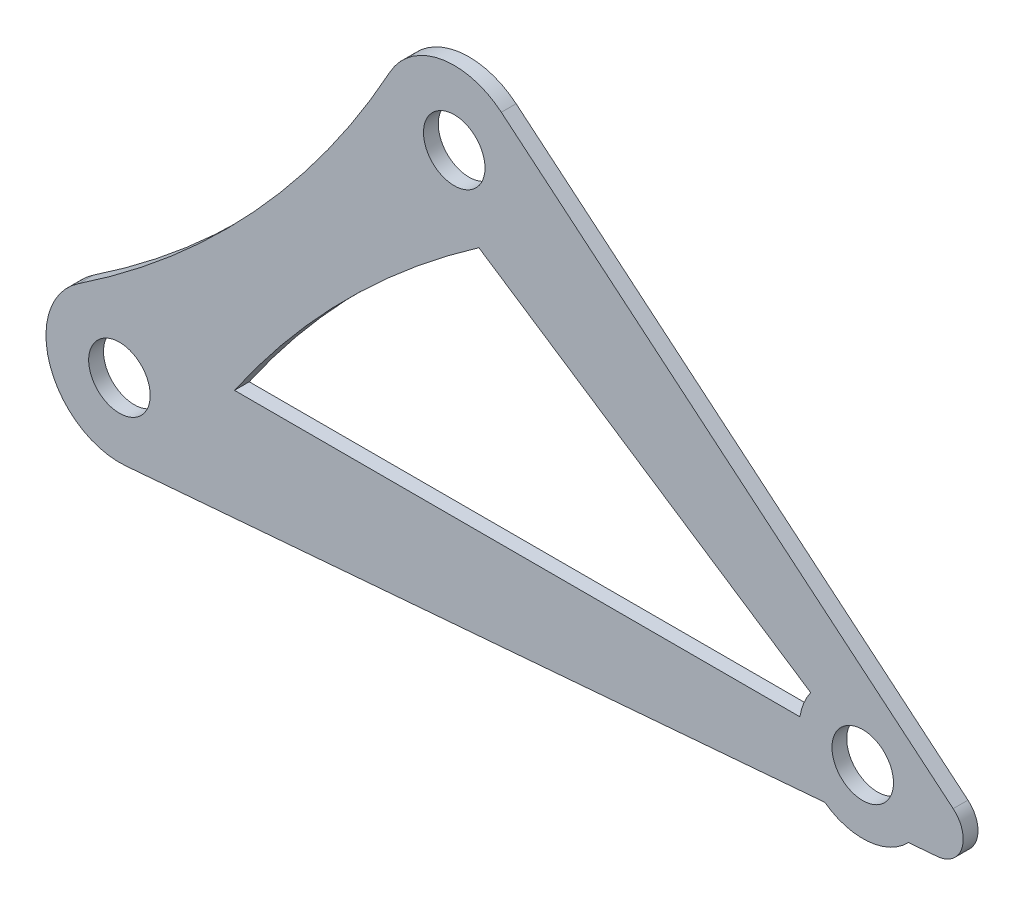
SolidWorks part; units mm, degrees
ref_plane "Plan de face" through (0, 0, 0) normal (1, 0, 0) x (0, 1, 0)
ref_plane "Plan de dessus" through (0, 0, 0) normal (0, 0, 1) x (0, 1, 0)
ref_plane "Plan de droite" through (0, 0, 0) normal (0, 1, 0) x (-1, 0, 0)
sketch "Esquisse1" plane through (0, 0, 0) normal (0, 0, 1) x (0, 1, 0)
  line L0 (0, 0) -> (0, 95.09) construction
  line L1 (0, 95.09) -> (39.1116, 59.1602) construction
  line L2 (39.1116, 59.1602) -> (0, 0) construction
  line L3 (0, 0) -> (19.5558, 77.1251) construction
  line L7 (0, 0) -> (-7.8578, 94.4362)
  line L8 (0, 0) -> (45.1649, 54.1073)
  line L9 (31.5783, 56.8316) -> (5.8767, 17.9555)
  line L10 (5, 18.4299) -> (5, 88.993)
  line L11 (34.9407, 61.9176) -> (5, 16.6293) construction
  line L13 (5, 16.6293) -> (5, 95.09) construction
  circle A0 centre (0, 95.09) radius 3.302
  circle A1 centre (39.1116, 59.1602) radius 3.302
  circle A3 centre (0, 95.09) radius 7.885
  circle A4 centre (39.1116, 59.1602) radius 7.885
  circle A6 centre (3.885, 15.3218) radius 3.302
  circle A7 centre (3.885, 15.3218) radius 3.885 construction
  circle A8 centre (3.885, 15.3218) radius 6.836
  arc A9 (42.9154, 66.067) -> (6.5601, 99.4647) centre (93.0851, 157.1659) cw
  arc A10 (32.5515, 54.7854) -> (-3.8037, 88.1831) centre (-53.9735, -2.9157) ccw
  dimension "D4" = 6.604
  dimension "D5" = 7.77
  dimension "D6" = 15.77
  dimension "D9" = 104
  dimension "D1" = 95.09
  dimension "D2" = 70.92
  dimension "D3" = 53.11
  dimension "D8" = 5
extrude "Boss.-Extru.2" add sketch "Esquisse1" along normal blind 1.587 contours L7 A8 | L10 A10 A3 L7 A8 | A4 A1 | A10 L9 A4 A9 A3 L10 | A10 L10 A3 | A3 A0 | L9 A8 L10 A6 | L10 A8 L7 L9 A6 | A4 A10 L9 A8 L7 L8 | A10 A4 L9 | A8 L7 L8
fillet "Congé1" radius 3 1 edges at (0, 0, 0.7935)
